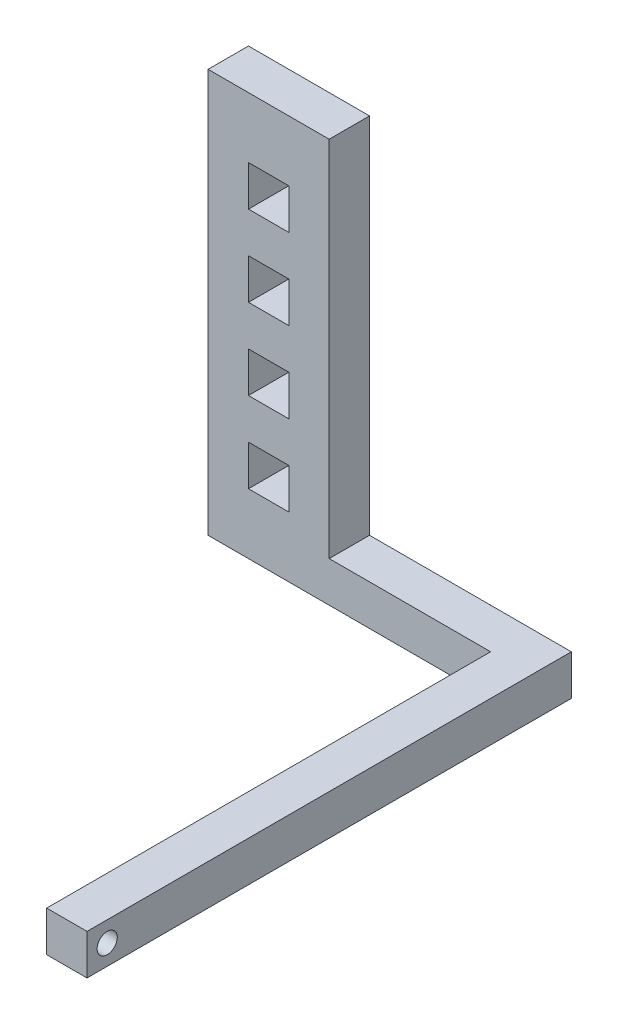
SolidWorks part; units mm, degrees
ref_plane "정면" through (0, 0, 0) normal (0, 0, 1) x (1, 0, 0)
ref_plane "윗면" through (0, 0, 0) normal (0, 1, 0) x (1, 0, 0)
ref_plane "우측면" through (0, 0, 0) normal (1, 0, 0) x (0, 0, -1)
sketch "스케치1" plane through (0, 0, 0) normal (0, 0, 1) x (1, 0, 0)
  line L0 (0, 50) -> (0, -50) construction
  line L1 (-15, 50) -> (15, 50)
  line L2 (-15, 50) -> (-15, -50)
  line L3 (-15, -50) -> (15, -50)
  line L4 (15, 50) -> (15, -50)
  line L5 (-15, 0) -> (15, 0) construction
  line L6 (-5, 15) -> (5, 15)
  line L7 (-5, 35) -> (5, 35)
  line L8 (-5, 35) -> (-5, 25)
  line L9 (-5, 25) -> (5, 25)
  line L10 (5, 35) -> (5, 25)
  line L11 (-5, 15) -> (-5, 5)
  line L12 (-5, 5) -> (5, 5)
  line L13 (5, 15) -> (5, 5)
  line L14 (-5, -5) -> (5, -5)
  line L15 (-5, -5) -> (-5, -15)
  line L16 (-5, -15) -> (5, -15)
  line L17 (5, -5) -> (5, -15)
  line L18 (-5, -25) -> (5, -25)
  line L19 (-5, -25) -> (-5, -35)
  line L20 (-5, -35) -> (5, -35)
  line L21 (5, -25) -> (5, -35)
  point P13 (0, 35)
  point P20 (0, 15)
  point P25 (0, -5)
  point P30 (0, -25)
  dimension "D1" = 100
  dimension "D2" = 30
  dimension "D3" = 10
  dimension "D4" = 10
  dimension "D5" = 15
  dimension "D6" = 4
extrude "보스-돌출1" add sketch "스케치1" along normal blind 10
sketch "스케치2" plane through (15, 0, 0) normal (1, 0, 0) x (0, 0, -1)
  line L0 (0, -50) -> (0, 50) construction
  line L1 (-10, -50) -> (0, -50)
  line L2 (-10, -50) -> (-10, -39.986)
  line L3 (-10, -39.986) -> (0, -39.986)
  line L4 (0, -50) -> (0, -39.986)
extrude "보스-돌출2" add sketch "스케치2" along normal blind 50
sketch "스케치3" plane through (65, 0, 0) normal (1, 0, 0) x (0, 0, -1)
  line L0 (-120, -44.986) -> (-103.4009, -44.986) construction
  line L1 (0, -39.986) -> (-120, -39.986)
  line L2 (0, -39.986) -> (0, -49.986)
  line L3 (0, -49.986) -> (-120, -49.986)
  line L4 (-120, -39.986) -> (-120, -49.986)
  circle A0 centre (-115, -44.986) radius 2.5
  dimension "D2" = 5
  dimension "D1" = 120
  dimension "D3" = 5
  dimension "D4" = 10
extrude "보스-돌출3" add sketch "스케치3" against normal blind 10
